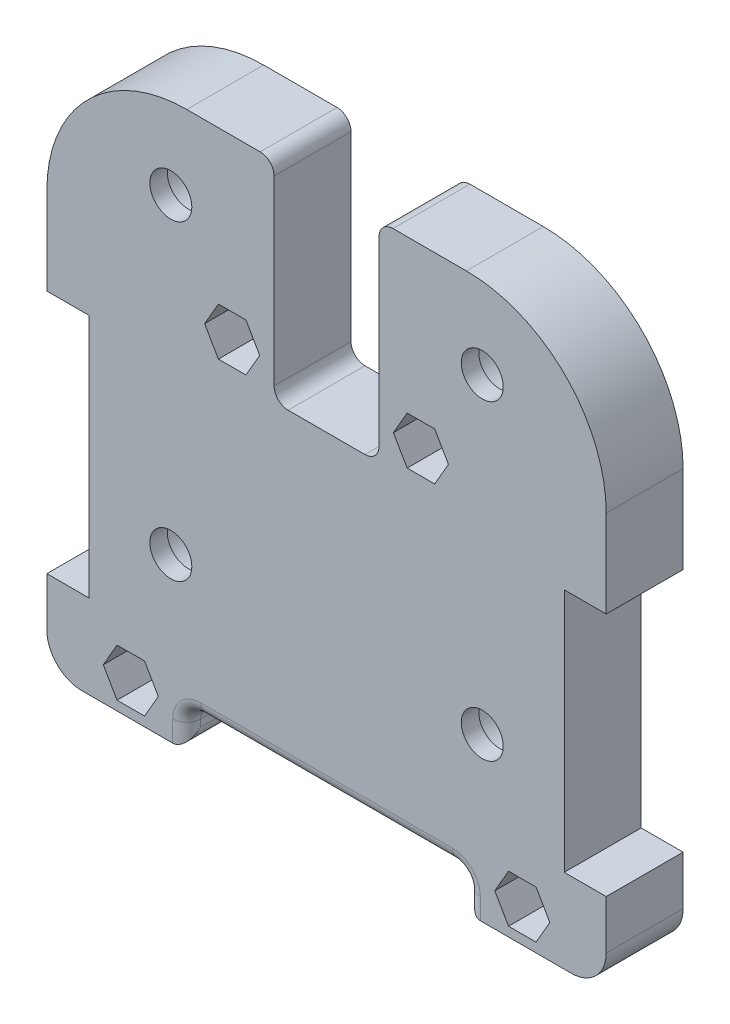
SolidWorks part; units mm, degrees
material "ABS"
ref_plane "前视基准面" through (0, 0, 0) normal (0, 0, 1) x (1, 0, 0)
ref_plane "上视基准面" through (0, 0, 0) normal (0, 1, 0) x (1, 0, 0)
ref_plane "右视基准面" through (0, 0, 0) normal (1, 0, 0) x (0, 0, -1)
sketch "草图1" plane through (0, 0, 0) normal (0, 0, 1) x (1, 0, 0)
  line L0 (0, 0) -> (0, 36.8895) construction
  line L2 (-40, 50) -> (40, 50)
  line L3 (-40, 50) -> (-40, -50)
  line L4 (-40, -50) -> (40, -50)
  line L5 (40, 50) -> (40, -50)
  dimension "D1" = 80
  dimension "D2" = 100
  dimension "D3" = 40
  dimension "D4" = 50
extrude "凸台-拉伸1" add sketch "草图1" along normal blind 11 contours L2 L5 L4 L3
sketch "草图7" plane through (0, 0, 11) normal (0, 0, 1) x (1, 0, 0)
  line L0 (0, 0) -> (0, 50) construction
  line L1 (-40, 50) -> (40, 50) construction
  line L3 (-7.5, 50) -> (7.5, 50)
  line L4 (-7.5, 50) -> (-7.5, 20)
  line L5 (-7.5, 20) -> (7.5, 20)
  line L6 (7.5, 50) -> (7.5, 20)
  dimension "D1" = 30
  dimension "D2" = 15
  dimension "D3" = 7.5
extrude "切除-拉伸1" cut sketch "草图7" against normal blind 16
sketch "草图2" plane through (0, 0, 11) normal (0, 0, 1) x (1, 0, 0)
  line L0 (0, 0) -> (0, -50) construction
  line L1 (-40, -50) -> (40, -50) construction
  line L2 (-23.6474, -14.5) -> (32.5152, -14.5) construction
  line L3 (-25.0117, -34.5) -> (44.0357, -34.5) construction
  line L4 (-19.0329, -14.5) -> (-17.8955, -14.5)
  line L5 (17.8955, -14.5) -> (19.0329, -14.5)
  line L6 (17.8955, -34.5) -> (19.0329, -34.5)
  line L7 (-19.0329, -34.5) -> (-17.8955, -34.5)
  arc A0 (-17.8955, -14.5) -> (-17.8955, -34.5) centre (0, -24.5) ccw
  arc A1 (-19.0329, -14.5) -> (-19.0329, -34.5) centre (0, -24.5) ccw
  arc A2 (17.8955, -34.5) -> (17.8955, -14.5) centre (0, -24.5) ccw
  arc A3 (19.0329, -34.5) -> (19.0329, -14.5) centre (0, -24.5) ccw
  dimension "D1" = 25.5
  dimension "D2" = 10
  dimension "D4" = 21.5
  dimension "D5" = 20.5
  dimension "D3" = 20
sketch "草图5" plane through (0, 0, 0) normal (0, 0, -1) x (-1, 0, 0)
  line L0 (0, 30) -> (0, -50) construction
  line L2 (40, -50) -> (-40, -50) construction
  point P6 (-13.5, 24.75)
  point P7 (-28, -24.75)
  point P8 (28, -24.75)
  point P9 (13.5, 24.75)
  dimension "D1" = 13.5
  dimension "D2" = 28
  dimension "D3" = 49.5
  dimension "D4" = 24.75
hole_wizard "M4 螺纹孔1" positions "3D草图2" profile "草图6" tap size "M4" standard "GB" end condition up to next
sketch3d "3D草图2"
  point P0 (13.5, 24.75, 0)
  point P3 (-13.5, 24.75, 0)
  point P6 (-28, -24.75, 0)
  point P9 (28, -24.75, 0)
sketch "草图6" plane through (13.5, 24.75, 0) normal (1, 0, 0) x (0, 1, 0)
  line L0 (0, 0) -> (0, 11)
  line L1 (0, 11) -> (1.65, 11)
  line L2 (1.65, 11) -> (1.65, 0.375)
  line L3 (1.65, 0.375) -> (2.025, 0)
  line L5 (2.025, 0) -> (0, 0)
  line L6 (-1.65, 0.375) -> (-2.025, 0) construction
  line L11 (0, -6.35) -> (0, 107.95) construction
  dimension "通孔螺纹孔钻头直径" = 3.3
  dimension "通孔螺纹孔钻头深度" = 11
  dimension "近端锥形沉头孔直径" = 4.05
  dimension "近端锥形沉头孔角度" = 90
cosmetic thread "孔螺蚊线1" parameters "D2"=4
cosmetic thread "孔螺蚊线2" parameters "D2"=4
cosmetic thread "孔螺蚊线3" parameters "D2"=4
cosmetic thread "孔螺蚊线4" parameters "D2"=4
fillet "圆角1" radius 20 2 edges at (40, 50, 5.5) (-40, 50, 5.5)
fillet "圆角2" radius 2 6 edges at (40, -50, 5.5) (-40, -50, 5.5) (-7.5, 50, 5.5) (-7.5, 20, 5.5) (7.5, 20, 5.5) (7.5, 50, 5.5)
sketch "草图9" plane through (0, 0, 0) normal (0, 0, 1) x (1, 0, 0)
  line L0 (40, 17.5) -> (34, 17.5)
  line L1 (40, 30) -> (40, -48) construction
  line L2 (34, 17.5) -> (34, -17.5)
  line L3 (40, 17.5) -> (40, -17.5)
  line L4 (0, 0) -> (46.0009, 0) construction
  line L5 (40, -17.5) -> (34, -17.5)
  line L6 (0, 0) -> (0, 43.2165) construction
  line L7 (-40, -17.5) -> (-34, -17.5)
  line L8 (-34, 17.5) -> (-34, -17.5)
  line L9 (-40, 17.5) -> (-34, 17.5)
  line L10 (-40, 17.5) -> (-40, -17.5)
  point P12 (34, 0)
  dimension "D1" = 35
  dimension "D2" = 6
extrude "切除-拉伸2" cut sketch "草图9" along normal blind 11
sketch "草图11" plane through (0, 0, 0) normal (0, 0, 1) x (1, 0, 0)
  line L0 (0, 36.6897) -> (0, -57.9108) construction
  line L1 (0, 30) -> (0, -50) construction
  line L2 (0, 16) -> (-52.3712, 16) construction
  line L3 (0, 16) -> (-36.4685, 52.4685) construction
  circle A0 centre (0, 16) radius 31.5 construction
  circle A1 centre (-22.2739, 38.2739) radius 3
  circle A2 centre (22.2739, 38.2739) radius 3
  circle A3 centre (22.2739, -6.2739) radius 3
  circle A4 centre (-22.2739, -6.2739) radius 3
  point P20 (0, 16)
  dimension "D1" = 63
  dimension "D4" = 6
  dimension "D2" = 16
  dimension "D3" = 45
  dimension "D5" = 4
extrude "切除-拉伸4" cut sketch "草图11" along normal blind 15
sketch "草图12" plane through (0, 0, 0) normal (0, 0, 1) x (1, 0, 0)
  line L0 (0, 41.1031) -> (0, -79.5039) construction
  circle A4 centre (13.5, 24.75) radius 3.43
  circle A5 centre (28, -24.75) radius 3.43
  circle A6 centre (-28, -24.75) radius 3.43
  circle A7 centre (-13.5, 24.75) radius 3.43
  dimension "D1" = 6.86
  dimension "D2" = 6.86
sketch "草图13" plane through (0, 0, 11) normal (0, 0, 1) x (1, 0, 0)
  line L0 (0, 30) -> (0, -54.2815) construction
  line L1 (-19.4275, 33.3439) -> (-16.5812, 38.2739)
  line L2 (-16.5812, 38.2739) -> (-19.4275, 43.2039)
  line L3 (-19.4275, 43.2039) -> (-25.1202, 43.2039)
  line L4 (-25.1202, 43.2039) -> (-27.9665, 38.2739)
  line L5 (-27.9665, 38.2739) -> (-25.1202, 33.3439)
  line L6 (-25.1202, 33.3439) -> (-19.4275, 33.3439)
  line L7 (-19.4275, -11.2039) -> (-16.5812, -6.2739)
  line L8 (-16.5812, -6.2739) -> (-19.4275, -1.3439)
  line L9 (-19.4275, -1.3439) -> (-25.1202, -1.3439)
  line L10 (-25.1202, -1.3439) -> (-27.9665, -6.2739)
  line L11 (-27.9665, -6.2739) -> (-25.1202, -11.2039)
  line L12 (-25.1202, -11.2039) -> (-19.4275, -11.2039)
  line L13 (25.1202, -11.2039) -> (19.4275, -11.2039)
  line L14 (27.9665, -6.2739) -> (25.1202, -11.2039)
  line L15 (25.1202, -1.3439) -> (27.9665, -6.2739)
  line L16 (19.4275, -1.3439) -> (25.1202, -1.3439)
  line L17 (16.5812, -6.2739) -> (19.4275, -1.3439)
  line L18 (19.4275, -11.2039) -> (16.5812, -6.2739)
  line L19 (25.1202, 33.3439) -> (19.4275, 33.3439)
  line L20 (27.9665, 38.2739) -> (25.1202, 33.3439)
  line L21 (25.1202, 43.2039) -> (27.9665, 38.2739)
  line L22 (19.4275, 43.2039) -> (25.1202, 43.2039)
  line L23 (16.5812, 38.2739) -> (19.4275, 43.2039)
  line L24 (19.4275, 33.3439) -> (16.5812, 38.2739)
  circle A0 centre (-22.2739, 38.2739) radius 4.93 construction
  circle A1 centre (-22.2739, -6.2739) radius 4.93 construction
  circle A2 centre (22.2739, -6.2739) radius 4.93 construction
  circle A3 centre (22.2739, 38.2739) radius 4.93 construction
  dimension "D1" = 9.86
  dimension "D2" = 9.86
sketch "草图15" plane through (0, 0, 11) normal (0, 0, 1) x (1, 0, 0)
  line L0 (0, 0) -> (0, 55.0159) construction
  circle A0 centre (-13.5, 24.75) radius 1.9
  circle A1 centre (-28, -24.75) radius 1.9
  circle A2 centre (13.5, 24.75) radius 1.9
  circle A3 centre (28, -24.75) radius 1.9
  dimension "D1" = 3.8
  dimension "D2" = 3.8
extrude "切除-拉伸8" cut sketch "草图15" against normal blind 14
sketch "草图16" plane through (0, 0, 0) normal (0, 0, -1) x (-1, 0, 0)
  line L0 (0, 0) -> (0, -36.2047) construction
  line L1 (0, 30) -> (0, -54.2815) construction
  circle A0 centre (-22.2739, 38.2739) radius 4.52
  circle A1 centre (-22.2739, -6.2739) radius 4.52
  circle A2 centre (22.2739, -6.2739) radius 4.52
  circle A3 centre (22.2739, 38.2739) radius 4.52
  dimension "D1" = 9.04
  dimension "D2" = 9.04
extrude "切除-拉伸9" cut sketch "草图16" against normal blind 8.5
sketch "草图17" plane through (0, 0, 11) normal (0, 0, 1) x (1, 0, 0)
  line L0 (0, 15.9424) -> (0, -37.777) construction
  line L1 (-15.4688, 21.34) -> (-11.5312, 21.34)
  line L2 (-11.5312, 21.34) -> (-9.5625, 24.75)
  line L3 (-9.5625, 24.75) -> (-11.5312, 28.16)
  line L4 (-11.5312, 28.16) -> (-15.4688, 28.16)
  line L5 (-15.4688, 28.16) -> (-17.4375, 24.75)
  line L6 (-17.4375, 24.75) -> (-15.4688, 21.34)
  line L7 (-26.0312, -28.16) -> (-24.0625, -24.75)
  line L8 (-24.0625, -24.75) -> (-26.0312, -21.34)
  line L9 (-26.0312, -21.34) -> (-29.9688, -21.34)
  line L10 (-29.9688, -21.34) -> (-31.9375, -24.75)
  line L11 (-31.9375, -24.75) -> (-29.9688, -28.16)
  line L12 (-29.9688, -28.16) -> (-26.0312, -28.16)
  line L13 (0, 41.1031) -> (0, -79.5039) construction
  line L14 (29.9688, -28.16) -> (26.0312, -28.16)
  line L15 (31.9375, -24.75) -> (29.9688, -28.16)
  line L16 (29.9688, -21.34) -> (31.9375, -24.75)
  line L17 (26.0312, -21.34) -> (29.9688, -21.34)
  line L18 (24.0625, -24.75) -> (26.0312, -21.34)
  line L19 (26.0312, -28.16) -> (24.0625, -24.75)
  line L20 (17.4375, 24.75) -> (15.4688, 21.34)
  line L21 (15.4688, 28.16) -> (17.4375, 24.75)
  line L22 (11.5312, 28.16) -> (15.4688, 28.16)
  line L23 (9.5625, 24.75) -> (11.5312, 28.16)
  line L24 (11.5312, 21.34) -> (9.5625, 24.75)
  line L25 (15.4688, 21.34) -> (11.5312, 21.34)
  circle A0 centre (-13.5, 24.75) radius 3.41 construction
  circle A1 centre (-28, -24.75) radius 3.41 construction
  circle A2 centre (28, -24.75) radius 3.41 construction
  circle A3 centre (13.5, 24.75) radius 3.41 construction
  dimension "D1" = 6.82
  dimension "D2" = 6.82
extrude "切除-拉伸10" cut sketch "草图17" against normal blind 8.5
sketch "草图18" plane through (0, 0, 11) normal (0, 0, 1) x (1, 0, 0)
  line L0 (-40, -17.5) -> (-34, -17.5) construction
  line L1 (-52.2252, -29.5) -> (-20, -29.5)
  line L2 (-52.2252, -29.5) -> (-52.2252, -55.0826)
  line L3 (-52.2252, -55.0826) -> (49.1366, -55.0826)
  line L4 (49.1366, -29.5) -> (49.1366, -55.0826)
  line L5 (0, 0) -> (0, -48.7042) construction
  line L6 (20, -29.5) -> (49.1366, -29.5)
  line L7 (-20, -24.5) -> (20, -24.5)
  line L8 (-20, -24.5) -> (-20, -29.5)
  line L10 (20, -24.5) -> (20, -29.5)
  point P10 (20, -27)
  dimension "D2" = 20
  dimension "D1" = 12
  dimension "D3" = 20
  dimension "D4" = 5
extrude "切除-拉伸11" cut sketch "草图18" against normal blind 13.5
ref_plane "基准面1" through (-40, -29.5, 0) normal (0, 0, 1) x (1, 0, 0)
fillet "圆角4" radius 5 2 edges at (40, -29.5, 5.5) (-40, -29.5, 5.5)
fillet "圆角5" radius 2 10 edges at (20, -27, 0) (-20, -27, 0) (-20, -27, 11) (20, -27, 11) (0, -24.5, 0) (-20, -24.5, 5.5) (0, -24.5, 11) (20, -24.5, 5.5) (20, -29.5, 5.5) (-20, -29.5, 5.5)
